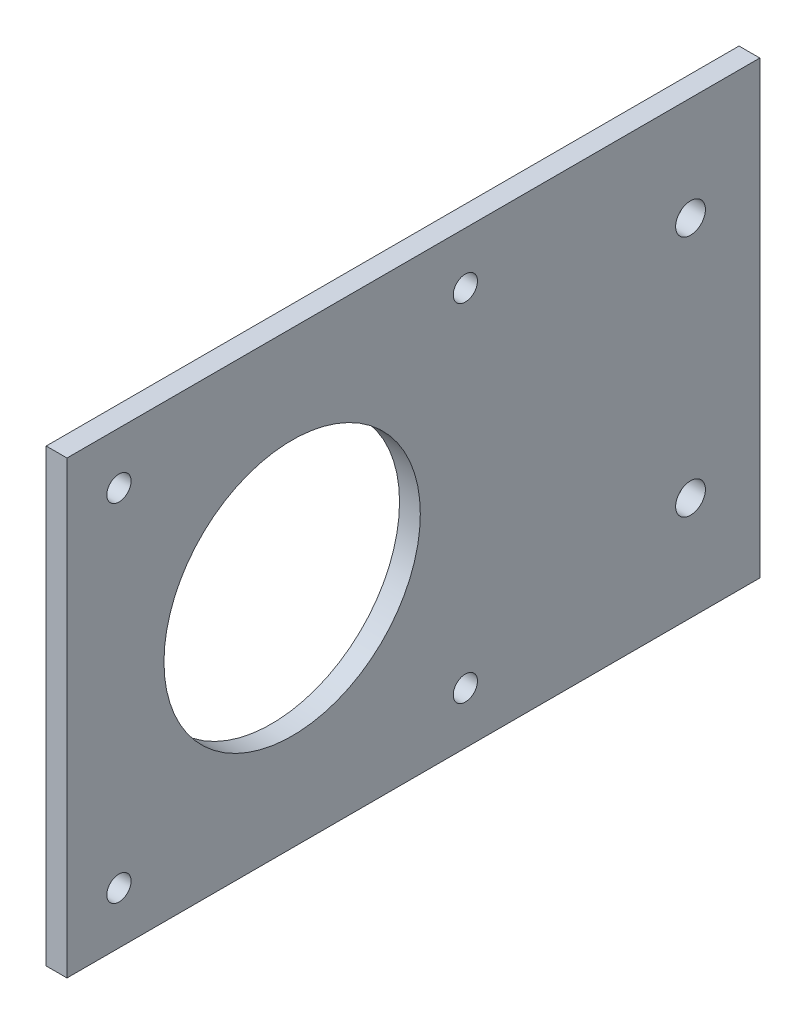
SolidWorks part; units mm, degrees
ref_plane "Front Plane" through (0, 0, 0) normal (0, 0, 1) x (1, 0, 0)
ref_plane "Top Plane" through (0, 0, 0) normal (0, 1, 0) x (1, 0, 0)
ref_plane "Right Plane" through (0, 0, 0) normal (1, 0, 0) x (0, 0, -1)
sketch "Sketch1" plane through (0, 0, 0) normal (1, 0, 0) x (0, 0, -1)
  line L1 (0, 0) -> (100, 0)
  line L2 (0, 0) -> (0, 65)
  line L3 (0, 65) -> (100, 65)
  line L4 (100, 0) -> (100, 65)
  line L6 (90, 65) -> (90, 0) construction
  circle A0 centre (32.5, 32.5) radius 18.5
  circle A5 centre (90, 50) radius 2.15
  circle A6 centre (90, 15) radius 2.15
  circle A7 centre (7.5, 57.5) radius 1.75
  circle A8 centre (57.5, 57.5) radius 1.75
  circle A9 centre (7.5, 7.5) radius 1.75
  circle A10 centre (57.5, 7.5) radius 1.75
  dimension "D3" = 37
  dimension "D12" = 4.3
  dimension "D13" = 4.3
  dimension "D4" = 3.5
  dimension "D5" = 3.5
  dimension "D6" = 3.5
  dimension "D7" = 3.5
  dimension "D1" = 100
  dimension "D2" = 65
  dimension "D14" = 10
  dimension "D15" = 15
  dimension "D16" = 15
  dimension "D8" = 50
  dimension "D9" = 50
  dimension "D10" = 25
  dimension "D11" = 25
  dimension "D17" = 7.5
  dimension "D18" = 7.5
extrude "Boss-Extrude1" add sketch "Sketch1" along normal blind 3
equation "\"D5@Sketch1\"=\"D4@Sketch1\""
equation "\"D6@Sketch1\"=\"D4@Sketch1\""
equation "\"D7@Sketch1\"=\"D4@Sketch1\""
